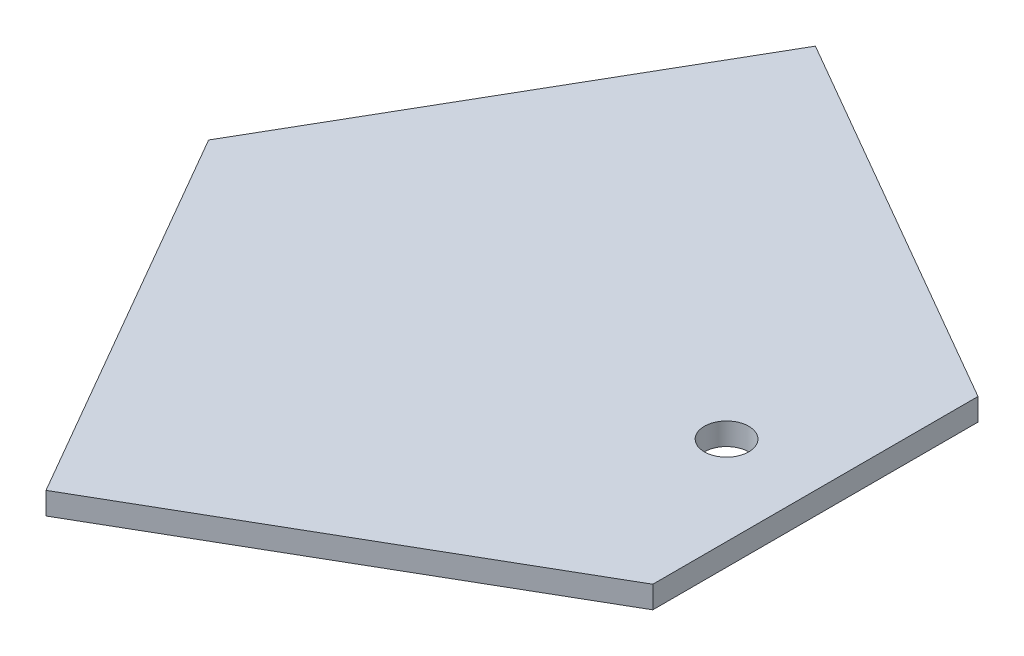
SolidWorks part; units mm, degrees
material "1.0037 (S235JR)"
ref_plane "Plan de face" through (0, 0, 0) normal (0, 0, 1) x (1, 0, 0)
ref_plane "Plan de dessus" through (0, 0, 0) normal (0, 1, 0) x (1, 0, 0)
ref_plane "Plan de droite" through (0, 0, 0) normal (1, 0, 0) x (0, 0, -1)
sketch "Esquisse1" plane through (0, 0, 0) normal (0, 1, 0) x (1, 0, 0)
  line L0 (0, 0) -> (50, -86.6025)
  line L1 (50, -86.6025) -> (136.6025, -36.6025)
  line L3 (50, 86.6025) -> (0, 0)
  line L4 (50, 86.6025) -> (136.6025, 36.6025)
  line L5 (136.6025, 36.6025) -> (136.6025, -36.6025)
  point P7 (136.6025, 0)
  dimension "D1" = 120
  dimension "D2" = 100
  dimension "D3" = 100
  dimension "D4" = 100
  dimension "D5" = 100
  dimension "D6" = 90
extrude "Boss.-Extru.1" add sketch "Esquisse1" along normal blind 5
sketch "Esquisse2" plane through (0, 5, 0) normal (0, 1, 0) x (1, 0, 0)
  line L0 (136.6025, -36.6025) -> (136.6025, 36.6025) construction
  circle A0 centre (116.6025, 0) radius 5
  dimension "D1" = 10
  dimension "D2" = 20
extrude "Enlèv. mat.-Extru.1" cut sketch "Esquisse2" against normal blind 10
